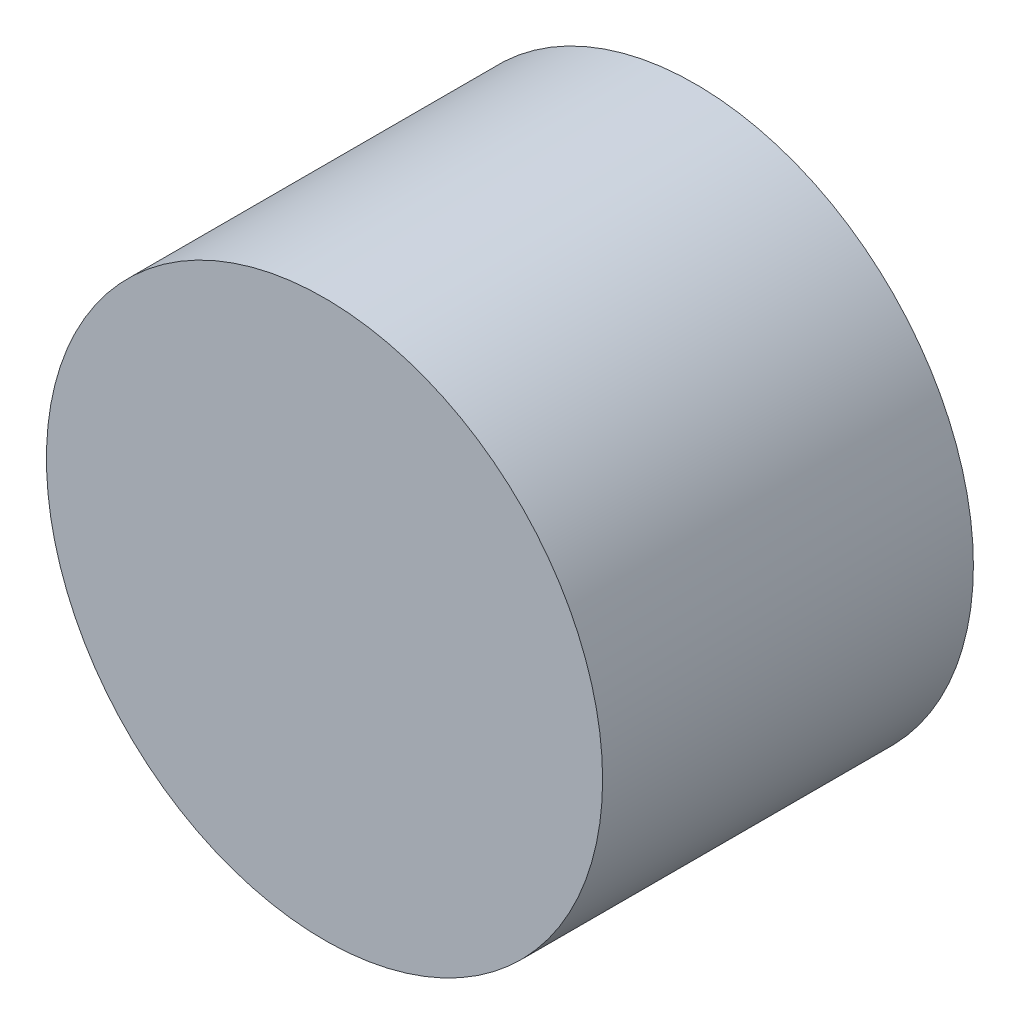
SolidWorks part; units mm, degrees
ref_plane "正面" through (0, 0, 0) normal (0, 0, 1) x (1, 0, 0)
ref_plane "平面" through (0, 0, 0) normal (0, 1, 0) x (1, 0, 0)
ref_plane "右側面" through (0, 0, 0) normal (1, 0, 0) x (0, 0, -1)
sketch "ｽｹｯﾁ1" plane through (0, 0, 0) normal (0, 0, 1) x (1, 0, 0)
  circle A0 centre (0, 0) radius 30
  dimension "D1" = 60
extrude "ﾎﾞｽ - 押し出し1" add sketch "ｽｹｯﾁ1" along normal blind 40
